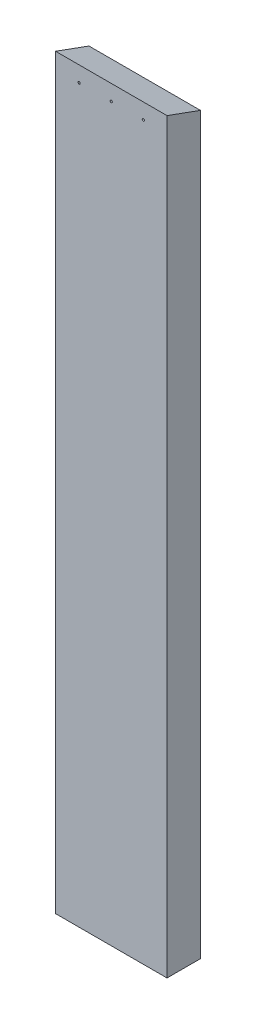
SolidWorks part; units mm, degrees
ref_plane "Front Plane" through (0, 0, 0) normal (0, 0, 1) x (1, 0, 0)
ref_plane "Top Plane" through (0, 0, 0) normal (0, 1, 0) x (1, 0, 0)
ref_plane "Right Plane" through (0, 0, 0) normal (1, 0, 0) x (0, 0, -1)
sketch "Sketch2" plane through (0, 0, 0) normal (0, 1, 0) x (1, 0, 0)
  line L0 (0, 0) -> (63.5, 19.05) construction
  line L1 (0, 0) -> (63.5, 0)
  line L2 (0, 0) -> (0, 19.05)
  line L3 (0, 19.05) -> (63.5, 19.05)
  line L4 (63.5, 0) -> (63.5, 19.05)
  circle A0 centre (31.75, 9.525) radius 3.9335 construction
  point P5 (31.75, 9.525)
  dimension "D1" = 63.5
  dimension "D2" = 19.05
extrude "Boss-Extrude1" add sketch "Sketch2" along normal blind 425.45
sketch "Sketch3" plane through (0, 0, 0) normal (0, -1, 0) x (1, 0, 0)
  line L0 (13.4874, -9.525) -> (50.0126, -9.525) construction
  circle A0 centre (13.4874, -9.525) radius 3.2004 construction
  circle A1 centre (13.4874, -9.525) radius 3.2004 construction
  circle A2 centre (13.4874, -9.525) radius 0.635
  circle A3 centre (31.75, -9.525) radius 0.635
  circle A4 centre (50.0126, -9.525) radius 0.635
  point P3 (31.75, -9.525)
  dimension "D1" = 1.27
extrude "Cut-Extrude1" cut sketch "Sketch3" against normal blind 50.8 and the other way through all
sketch "Sketch4" plane through (0, 0, 0) normal (0, 0, 1) x (1, 0, 0)
  line L0 (13.4366, 416.56) -> (31.7246, 416.56) construction
  line L2 (63.5, 425.45) -> (63.5, 0) construction
  line L5 (31.7246, 416.56) -> (31.7246, 396.9743) construction
  line L6 (31.7246, 416.56) -> (50.0126, 416.56) construction
  line L7 (0, 425.45) -> (63.5, 425.45) construction
  line L9 (50.0126, 0) -> (50.0126, 416.56) construction
  circle A1 centre (31.7246, 416.56) radius 0.635
  circle A3 centre (50.0126, 416.56) radius 0.635
  circle A4 centre (13.4366, 416.56) radius 0.635
  point P18 (50.0126, 0)
  dimension "D2" = 1.27
  dimension "D3" = 18.288
  dimension "D1" = 8.89
extrude "Cut-Extrude2" cut sketch "Sketch4" against normal through all
sketch "Sketch5" plane through (0, 0, 0) normal (-1, 0, 0) x (0, 0, 1)
  line L0 (0, 425.45) -> (-19.05, 418.5164)
  line L1 (-19.05, 425.45) -> (0, 425.45) construction
  line L2 (-19.05, 425.45) -> (-19.05, 0) construction
  line L3 (-19.05, 425.45) -> (-19.05, 418.5164)
  line L4 (-19.05, 425.45) -> (0, 425.45)
  dimension "D1" = 20
extrude "Cut-Extrude3" cut sketch "Sketch5" against normal through all
